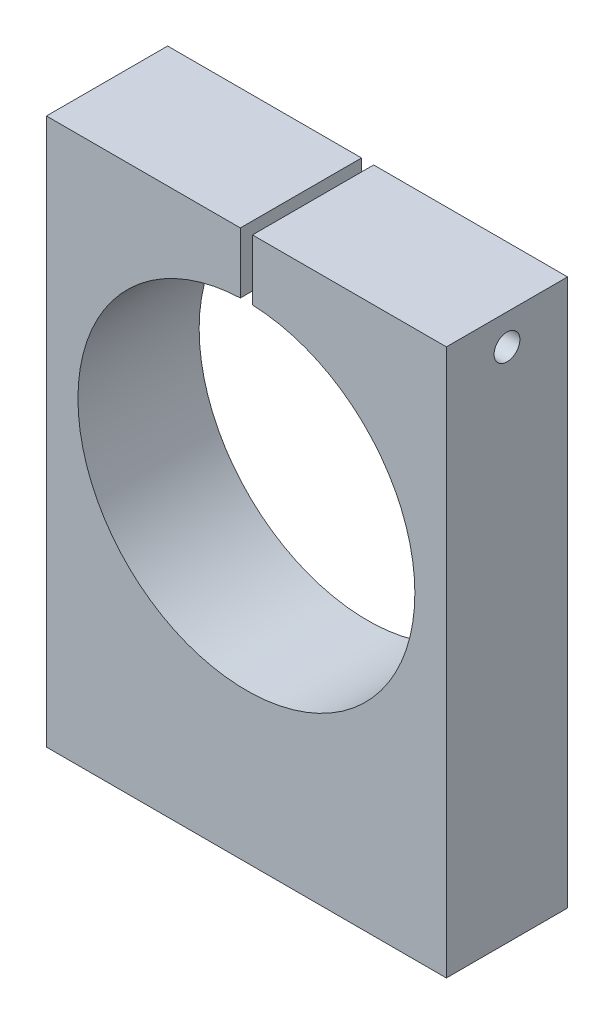
SolidWorks part; units mm, degrees
material "1060 Alloy"
ref_plane "Front Plane" through (0, 0, 0) normal (0, 0, 1) x (1, 0, 0)
ref_plane "Top Plane" through (0, 0, 0) normal (0, 1, 0) x (1, 0, 0)
ref_plane "Right Plane" through (0, 0, 0) normal (1, 0, 0) x (0, 0, -1)
sketch "Sketch1" plane through (0, 0, 0) normal (0, 0, 1) x (1, 0, 0)
  line L0 (0, 57.277) -> (0, 0) construction
  line L1 (-20.955, 0) -> (20.955, 0)
  line L2 (-20.955, 0) -> (-20.955, 57.277)
  line L3 (-20.955, 57.277) -> (20.955, 57.277)
  line L4 (20.955, 0) -> (20.955, 57.277)
  line L5 (-5.2521, 33.274) -> (9.7479, 33.274) construction
  line L8 (-5.2521, 25.052) -> (-5.2521, 41.496) construction
  line L9 (9.7479, 41.496) -> (9.7479, 25.052) construction
  circle A0 centre (0, 33.274) radius 17.653
  point P9 (0, 50.927)
  dimension "D4" = 35.306
  dimension "D1" = 41.91
  dimension "D2" = 6.35
extrude "Boss-Extrude1" add sketch "Sketch1" along normal mid plane 12.7
sketch "Sketch4" plane through (0, 57.277, 0) normal (0, 1, 0) x (1, 0, 0)
  line L0 (20.955, -6.35) -> (-20.955, -6.35) construction
  line L1 (-0.635, 6.35) -> (0.635, 6.35)
  line L2 (-0.635, 6.35) -> (-0.635, -6.35)
  line L3 (-0.635, -6.35) -> (0.635, -6.35)
  line L4 (0.635, 6.35) -> (0.635, -6.35)
  line L5 (-0.635, 6.35) -> (0.635, -6.35) construction
  line L6 (-0.635, -6.35) -> (0.635, 6.35) construction
  point P0 (0, 0)
  dimension "D1" = 1.27
extrude "Cut-Extrude1" cut sketch "Sketch4" against normal up to surface (6.3614 mm away)
sketch "Sketch9" plane through (-20.955, 0, 0) normal (-1, 0, 0) x (0, 0, 1)
  line L0 (-6.35, 50.9156) -> (6.35, 50.9156) construction
  line L1 (-6.35, 57.277) -> (-6.35, 0) construction
  line L2 (6.35, 57.277) -> (6.35, 0) construction
  line L3 (0, 57.277) -> (0, 50.9156) construction
  line L4 (6.35, 57.277) -> (-6.35, 57.277) construction
  circle A0 centre (0, 54.0963) radius 1.7859
  dimension "D1" = 3.5719
extrude "Cut-Extrude2" cut sketch "Sketch9" against normal up to surface (20.32 mm away) up to face at (-0.635, 54.0963, 0)
hole_wizard "#6-32 Tapped Hole1" positions "Sketch11" profile "Sketch10" tap size "#6-32" standard "Ansi Inch" end condition through all
sketch "Sketch11" plane through (0.635, 0, 0) normal (-1, 0, 0) x (0, 0, 1)
  line L0 (-1.7859, 54.0963) -> (1.7859, 54.0963) construction
  circle A0 centre (0, 54.0963) radius 1.7859 construction
  point P0 (0, 54.0963)
cosmetic thread "Hole Thread2" parameters "D2"=3.5052
sketch "Sketch10" plane through (0.635, 54.0963, 0) normal (0, 1, 0) x (0, 0, 1)
  line L0 (0, 0) -> (0, 20.32)
  line L1 (0, 20.32) -> (1.3525, 20.32)
  line L2 (1.3525, 20.32) -> (1.3525, 0)
  line L5 (1.3525, 0) -> (0, 0)
  line L11 (0, -6.35) -> (0, 107.95) construction
  dimension "Thru Tap Drill Dia." = 2.7051
  dimension "Thru Tap Drill Depth" = 20.32
hole_wizard "#4-40 Tapped Hole3" positions "Sketch13" profile "Sketch12" tap size "#4-40" standard "Ansi Inch"
sketch "Sketch13" plane through (0, 0, 0) normal (0, -1, 0) x (1, 0, 0)
  line L0 (-20.955, 0) -> (20.955, 0) construction
  line L1 (-20.955, 6.35) -> (-20.955, -6.35) construction
  line L2 (20.955, 6.35) -> (20.955, -6.35) construction
  point P0 (-14.605, 0)
  point P1 (14.605, 0)
  dimension "D1" = 6.35
  dimension "D2" = 6.35
sketch "Sketch12" plane through (-14.605, 0, 0) normal (1, 0, 0) x (0, 0, -1)
  line L0 (0, 0) -> (0, 13.3792)
  line L1 (0, 13.3792) -> (1.1303, 12.7)
  line L2 (1.1303, 12.7) -> (1.1303, 0)
  line L5 (1.1303, 0) -> (0, 0)
  line L10 (0, 13.3792) -> (-1.1303, 12.7) construction
  line L11 (0, -6.35) -> (0, 107.95) construction
  dimension "Tap Drill Dia." = 2.2606
  dimension "Tap Drill Depth" = 12.7
  dimension "Drill Angle" = 118
cosmetic thread "Hole Thread3" parameters "D1"=5.6896, "D2"=2.8448
cosmetic thread "Hole Thread4" parameters "D1"=5.6896, "D2"=2.8448
